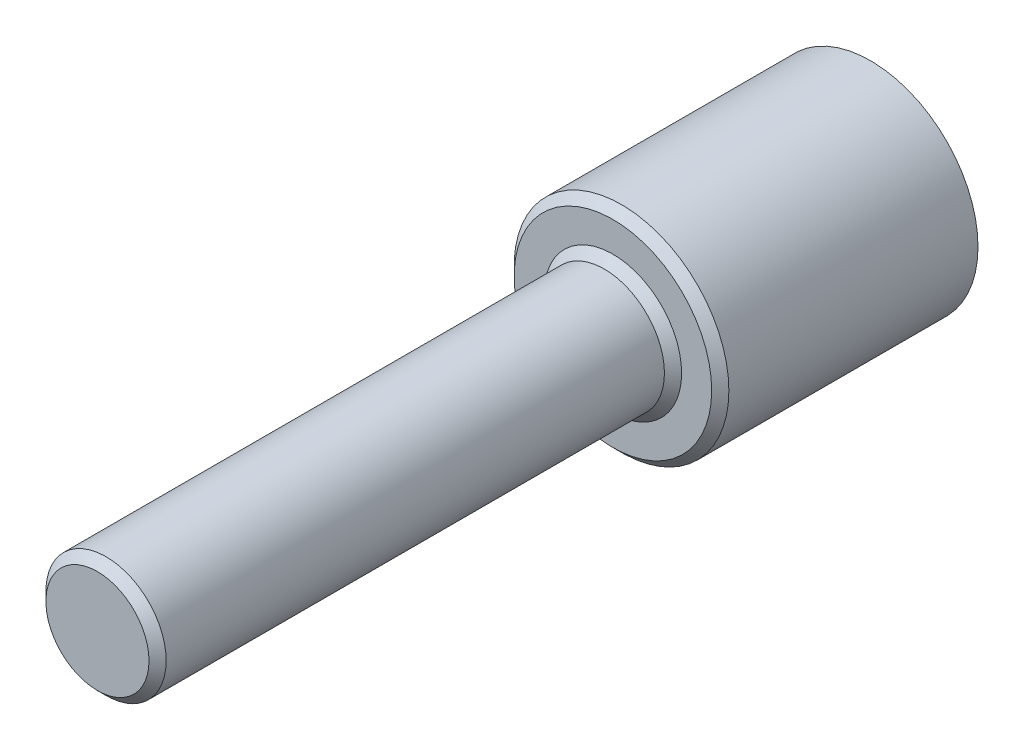
SolidWorks part; units mm, degrees
material "6061-T6 (SS)"
ref_plane "Front" through (0, 0, 0) normal (0, 0, 1) x (1, 0, 0)
ref_plane "Top" through (0, 0, 0) normal (0, 1, 0) x (1, 0, 0)
ref_plane "Right" through (0, 0, 0) normal (1, 0, 0) x (0, 0, -1)
sketch "Sketch1" plane through (0, 0, 0) normal (0, 0, 1) x (1, 0, 0)
  circle A0 centre (0, 0) radius 3.9688
  dimension "D1" = 7.9375
extrude "Boss-Extrude1" add sketch "Sketch1" along normal blind 28.575
sketch "Sketch2" plane through (0, 0, 28.575) normal (0, 0, 1) x (1, 0, 0)
  circle A0 centre (0, 0) radius 2.2225
  circle A1 centre (0, 0) radius 8.8206
  circle M1 centre (0, 0) radius 3.9688
  dimension "D1" = 4.445
extrude "Cut-Extrude1" cut sketch "Sketch2" against normal blind 19.05 contours A0 M1
sketch "Sketch3" plane through (0, 0, 0) normal (0, 0, -1) x (-1, 0, 0)
  circle A0 centre (0, 0) radius 2.4892
  dimension "D1" = 4.9784
extrude "Cut-Extrude2" cut sketch "Sketch3" against normal blind 7.62
chamfer "Chamfer1" distance 0.3175 angle 45 3 edges at (2.2225, 0, 28.575) (2.2225, 0, 9.525) (3.9688, 0, 9.525)
